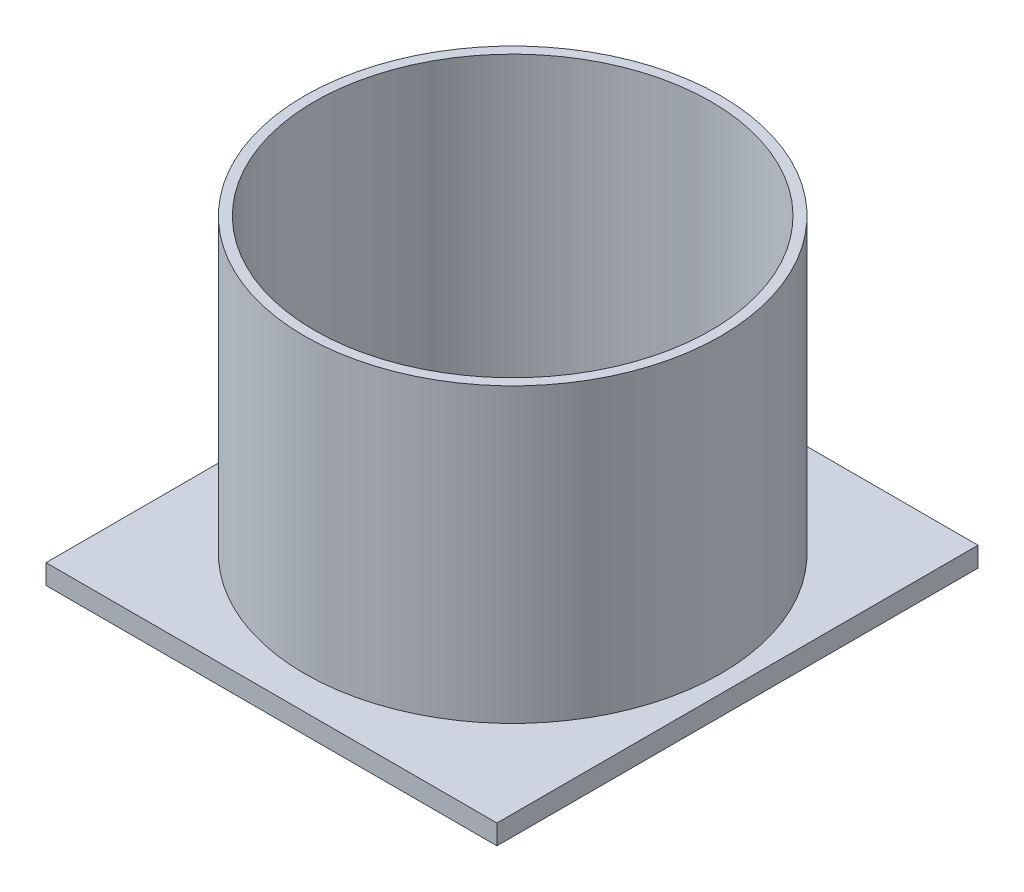
SolidWorks part; units mm, degrees
ref_plane "Alzado" through (0, 0, 0) normal (0, 0, 1) x (1, 0, 0)
ref_plane "Planta" through (0, 0, 0) normal (0, 1, 0) x (1, 0, 0)
ref_plane "Vista lateral" through (0, 0, 0) normal (1, 0, 0) x (0, 0, -1)
sketch "Croquis1" plane through (0, 0, 0) normal (0, 1, 0) x (1, 0, 0)
  line L0 (0, 0) -> (41.5, 0)
  line L1 (41.5, 0) -> (41.5, 44.4)
  line L2 (41.5, 44.4) -> (0, 44.4)
  line L3 (0, 44.4) -> (0, 0)
  dimension "D1" = 41.5
  dimension "D2" = 44.4
extrude "Saliente-Extruir1" add sketch "Croquis1" along normal blind 1.5
sketch "Croquis2" plane through (0, 1.5, 0) normal (0, 1, 0) x (1, 0, 0)
  line L0 (0, 44.4) -> (41.5, 0) construction
  line L1 (41.5, 0) -> (41.5, 44.4) construction
  line L2 (41.5, 44.4) -> (0, 0) construction
  line L3 (0, 0) -> (-2, -2.1398) construction
  line L4 (-2, -2.1398) -> (-2, 46.4) construction
  line L5 (-2, 46.4) -> (43.5, 46.4) construction
  line L6 (43.5, 46.4) -> (43.5, -2.1398) construction
  line L7 (-2, -2.1398) -> (43.5, -2.1398)
  line L8 (0, 44.4) -> (0, 0) construction
  line L9 (41.5, 44.4) -> (0, 44.4) construction
  line L11 (43.5, -2.1398) -> (43.5, 46.4)
  line L12 (43.5, 46.4) -> (-2, 46.4)
  line L13 (-2, 46.4) -> (-2, -2.1398)
  dimension "D1" = 2
  dimension "D2" = 2
  dimension "D3" = 2
extrude "Saliente-Extruir2" add sketch "Croquis2" along normal blind 2
sketch "Croquis3" plane through (0, 0, 0) normal (0, -1, 0) x (1, 0, 0)
  line L0 (0, 0) -> (41.5, -44.4) construction
  circle A0 centre (20.75, -22.2) radius 21
  point P6 (0, 0)
  point P7 (20.75, -22.2)
  dimension "D1" = 42
extrude "Saliente-Extruir3" add sketch "Croquis3" against normal blind 33
sketch "Croquis4" plane through (0, 33, 0) normal (0, 1, 0) x (1, 0, 0)
  circle A0 centre (20.75, 22.2) radius 20
  dimension "D1" = 40
extrude "Cortar-Extruir1" cut sketch "Croquis4" against normal through all
